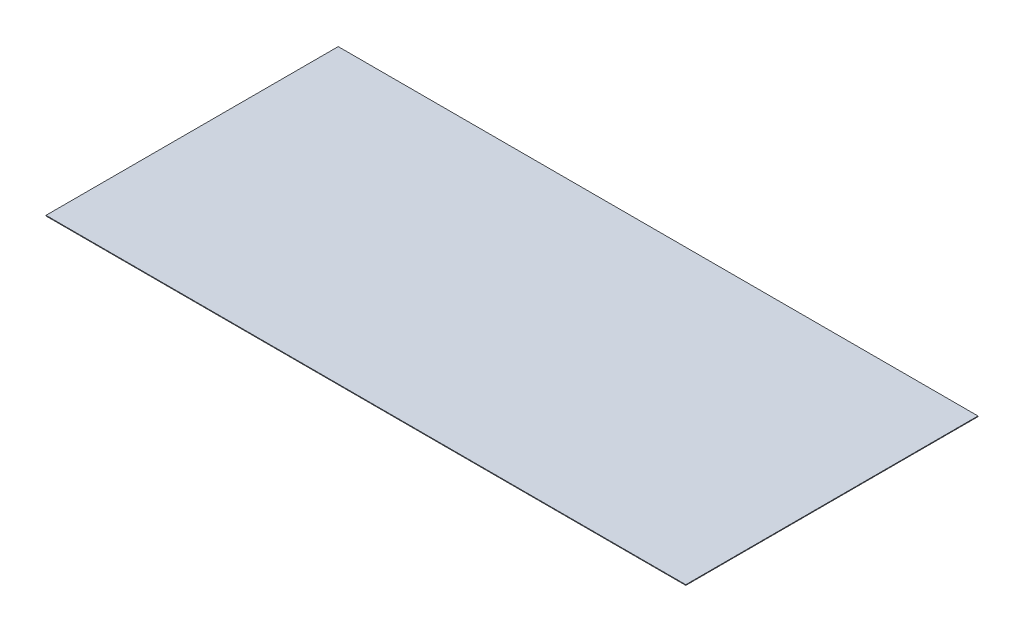
SolidWorks part; units mm, degrees
material "Silicium"
ref_plane "Plan de face" through (0, 0, 0) normal (0, 0, 1) x (1, 0, 0)
ref_plane "Plan de dessus" through (0, 0, 0) normal (0, 1, 0) x (1, 0, 0)
ref_plane "Plan de droite" through (0, 0, 0) normal (1, 0, 0) x (0, 0, -1)
sketch "Esquisse1" plane through (0, 0, 0) normal (0, 1, 0) x (1, 0, 0)
  line L1 (0, 227) -> (994, 227)
  line L2 (0, 227) -> (0, -227)
  line L3 (0, -227) -> (994, -227)
  line L4 (994, 227) -> (994, -227)
  dimension "D1" = 454
  dimension "D2" = 994
extrude "Boss.-Extru.1" add sketch "Esquisse1" along normal blind 1
